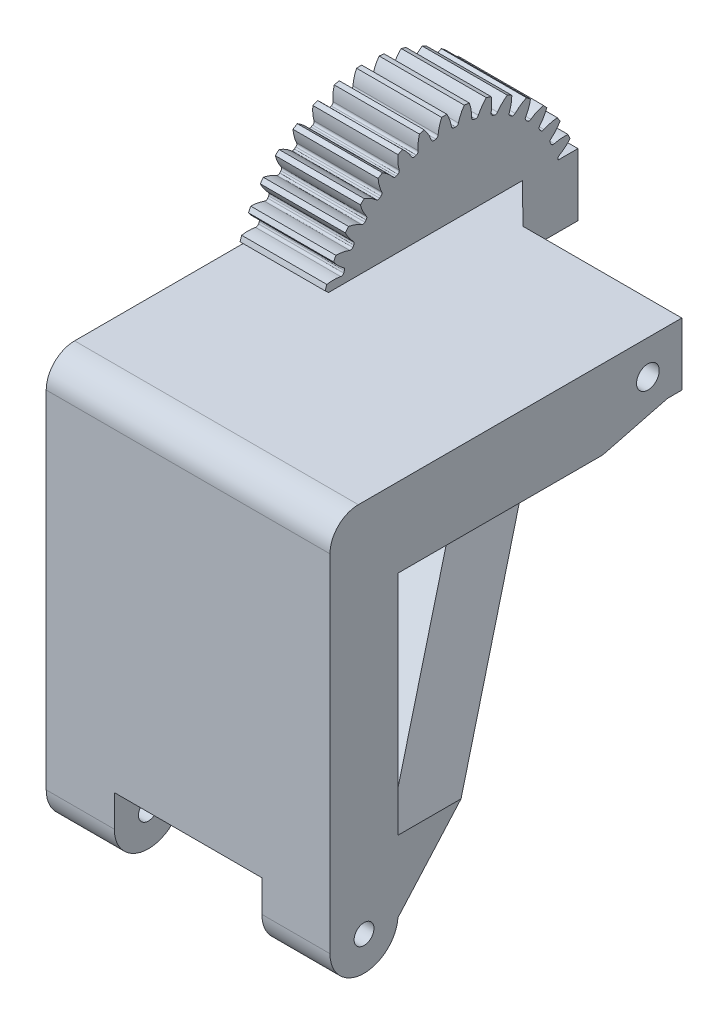
SolidWorks part; units mm, degrees
ref_plane "Front Plane" through (0, 0, 0) normal (0, 0, 1) x (1, 0, 0)
ref_plane "Top Plane" through (0, 0, 0) normal (0, 1, 0) x (1, 0, 0)
ref_plane "Right Plane" through (0, 0, 0) normal (1, 0, 0) x (0, 0, -1)
other "Graphic1"
sketch "Sketch2" plane through (0, 0, 0) normal (1, 0, 0) x (0, 0, -1)
  line L0 (-282, -50) -> (-282, 16.0062)
  line L1 (-282, 16.0062) -> (-203.3277, 16.0062)
  line L2 (-203.3277, 16.0062) -> (-203.3277, 4.9936)
  line L3 (-203.3277, 4.9936) -> (-222.5466, 4.9936)
  line L4 (-222.5466, 4.9936) -> (-233.9331, 2.0714)
  line L5 (-233.9331, 2.0714) -> (-233.9331, -9.6765)
  line L6 (-233.9331, -9.6765) -> (-270.0186, -50.4726)
  line L7 (-270.0186, 2.0714) -> (-270.0186, -35.8156)
  line L8 (-270.0186, -35.8156) -> (-240.3653, -2.4074)
  line L10 (-240.3653, -2.4074) -> (-240.3737, 1.8611)
  line L11 (-240.3737, 1.8611) -> (-270.0186, 2.0714)
  circle A0 centre (-276, -50) radius 1.75
  circle A1 centre (-226, 10) radius 2
  arc A2 (-282, -50) -> (-270.0186, -50.4726) centre (-276, -50) ccw
extrude "Boss-Extrude1" add sketch "Sketch2" along normal blind 47.5 and the other way blind 2.5 from offset 70
sketch "Sketch3" plane through (0, 0, 0) normal (0, 0, 1) x (1, 0, 0)
  line L0 (79.5, -55.8916) -> (79.5, -57.717)
  line L2 (79.5, -55.8916) -> (79.5, -44.4098)
  line L3 (79.5, -44.4098) -> (105.5, -44.4098)
  line L4 (105.5, -55.8916) -> (105.5, -44.4098)
  line L5 (79.5, -57.717) -> (105.5, -57.717)
  line L6 (105.5, -57.717) -> (105.5, -55.8916)
extrude "Cut-Extrude1" cut sketch "Sketch3" along normal through all
sketch "Sketch4" plane through (0, 0, 0) normal (0, 0, 1) x (1, 0, 0)
  line L0 (105.5, -44.4098) -> (94.3961, -22.2019)
  line L3 (90.6039, -22.2019) -> (79.5, -44.4098)
  line L4 (79.5, -44.4098) -> (105.5, -44.4098)
  line L5 (97.5, 2.0714) -> (117.5, -37.9286)
  line L6 (67.5, 2.0714) -> (117.5, 2.0714) construction
  line L7 (117.5, -50.4726) -> (117.5, -9.6765) construction
  line L8 (117.5, 2.0714) -> (97.5, 2.0714)
  line L9 (87.5, 2.0714) -> (67.5, 2.0714)
  line L10 (67.5, -9.6765) -> (67.5, 2.0714) construction
  line L11 (67.5, 2.0714) -> (67.5, -37.9286)
  line L12 (67.5, -50.4726) -> (67.5, -9.6765) construction
  line L13 (67.5, -37.9286) -> (87.5, 2.0714)
  line L14 (117.5, 2.0714) -> (117.5, -37.9286)
  line L15 (92.5, 16.0062) -> (92.5, -62.4116) construction
  line L16 (67.5, 16.0062) -> (117.5, 16.0062) construction
  line L17 (67.5, 16.0062) -> (67.5, -50) construction
  line L18 (117.5, 16.0062) -> (117.5, -50) construction
  arc A0 (94.3961, -22.2019) -> (90.6039, -22.2019) centre (92.5, -23.15) ccw
  dimension "D1" = 25
  dimension "D2" = 25
  dimension "D3" = 20
  dimension "D4" = 20
  dimension "D5" = 40
  dimension "D6" = 40
extrude "Cut-Extrude2" cut sketch "Sketch4" against normal blind 53 from surface at 270.0186 starting at face at (92.5, -16.8721, 270.0186)
fillet "Fillet1" radius 5 1 edges at (92.5, 16.0062, 282)
sketch "Sketch5" plane through (0, 16.0062, 0) normal (0, 1, 0) x (1, 0, 0)
  line L0 (65.0251, -220.0274) -> (95.5, -220.0314)
  line L1 (95.5, -220.0314) -> (102.5, -213.068)
  line L2 (102.5, -213.068) -> (102.5, -196.177)
  line L3 (102.5, -196.177) -> (65.0251, -196.177)
  line L4 (65.0251, -196.177) -> (65.0251, -220.0274)
extrude "Cut-Extrude3" cut sketch "Sketch5" against normal through all
sketch "Sketch7" plane through (117.5, 0, 0) normal (1, 0, 0) x (0, 0, -1)
  line L5 (-247.2493, 16.0062) -> (-206.8184, 16.0062)
  arc A0 (-222.9056, 32.589) -> (-222.459, 32.5234) centre (-226, 10) cw
  arc A1 (-221.7033, 29.6354) -> (-221.3907, 29.5644) centre (-226, 10) cw
  arc A2 (-219.0301, 31.7085) -> (-219.4613, 31.8423) centre (-226, 10) ccw
  arc A3 (-219.0301, 31.7085) -> (-218.6017, 31.5663) centre (-226, 10) cw
  arc A4 (-218.3589, 28.591) -> (-218.0634, 28.4667) centre (-226, 10) cw
  arc A5 (-215.3663, 30.1684) -> (-215.7678, 30.375) centre (-226, 10) ccw
  arc A6 (-215.3663, 30.1684) -> (-214.9691, 29.9539) centre (-226, 10) cw
  arc A7 (-215.2467, 26.9817) -> (-214.9773, 26.808) centre (-226, 10) cw
  arc A8 (-212.0257, 28.0155) -> (-212.3851, 28.2887) centre (-226, 10) ccw
  arc A9 (-212.0257, 28.0155) -> (-211.6717, 27.7353) centre (-226, 10) cw
  arc A10 (-212.4612, 24.8564) -> (-212.226, 24.6386) centre (-226, 10) cw
  arc A11 (-209.1096, 25.3152) -> (-209.4162, 25.6466) centre (-226, 10) ccw
  arc A12 (-209.1096, 25.3152) -> (-208.8097, 24.9778) centre (-226, 10) cw
  arc A13 (-210.0871, 22.2797) -> (-209.8933, 22.0244) centre (-226, 10) cw
  arc A14 (-206.7068, 22.1495) -> (-206.9511, 22.5292) centre (-226, 10) ccw
  arc A15 (-206.7068, 22.1495) -> (-206.47, 21.7652) centre (-226, 10) cw
  arc A16 (-208.1966, 19.3299) -> (-208.05, 19.0448) centre (-226, 10) cw
  arc A17 (-204.8901, 18.6147) -> (-205.0648, 19.031) centre (-226, 10) ccw
  arc A18 (-204.8901, 18.6147) -> (-204.7237, 18.1951) centre (-226, 10) cw
  arc A19 (-206.8469, 16.0966) -> (-206.8184, 16.0062) centre (-226, 10) cw
  arc A83 (-247.7085, 16.9699) -> (-247.8423, 16.5387) centre (-226, 10) ccw
  arc A84 (-247.7085, 16.9699) -> (-247.5663, 17.3984) centre (-226, 10) cw
  arc A85 (-244.591, 17.6411) -> (-244.4667, 17.9366) centre (-226, 10) cw
  arc A86 (-246.1684, 20.6337) -> (-246.375, 20.2323) centre (-226, 10) ccw
  arc A87 (-246.1684, 20.6337) -> (-245.9539, 21.0309) centre (-226, 10) cw
  arc A88 (-242.9817, 20.7533) -> (-242.808, 21.0228) centre (-226, 10) cw
  arc A89 (-244.0155, 23.9743) -> (-244.2887, 23.6149) centre (-226, 10) ccw
  arc A90 (-244.0155, 23.9743) -> (-243.7353, 24.3283) centre (-226, 10) cw
  arc A91 (-240.8564, 23.5388) -> (-240.6386, 23.774) centre (-226, 10) cw
  arc A92 (-241.3152, 26.8904) -> (-241.6466, 26.5838) centre (-226, 10) ccw
  arc A93 (-241.3152, 26.8904) -> (-240.9778, 27.1903) centre (-226, 10) cw
  arc A94 (-238.2797, 25.9129) -> (-238.0244, 26.1067) centre (-226, 10) cw
  arc A95 (-238.1495, 29.2932) -> (-238.5292, 29.0489) centre (-226, 10) ccw
  arc A96 (-238.1495, 29.2932) -> (-237.7652, 29.53) centre (-226, 10) cw
  arc A97 (-235.3299, 27.8035) -> (-235.0448, 27.95) centre (-226, 10) cw
  arc A98 (-234.6147, 31.1099) -> (-235.031, 30.9352) centre (-226, 10) ccw
  arc A99 (-234.6147, 31.1099) -> (-234.1951, 31.2763) centre (-226, 10) cw
  arc A100 (-232.0966, 29.1531) -> (-231.7904, 29.2479) centre (-226, 10) cw
  arc A101 (-230.8182, 32.2851) -> (-231.2585, 32.1853) centre (-226, 10) ccw
  arc A102 (-230.8182, 32.2851) -> (-230.376, 32.3761) centre (-226, 10) cw
  arc A103 (-228.6781, 29.9208) -> (-228.3601, 29.961) centre (-226, 10) cw
  arc A104 (-226.8752, 32.7832) -> (-227.3261, 32.7614) centre (-226, 10) ccw
  arc A105 (-226.8752, 32.7832) -> (-226.4239, 32.7961) centre (-226, 10) cw
  arc A106 (-225.1782, 30.0832) -> (-224.858, 30.0675) centre (-226, 10) cw
  arc A107 (-222.9056, 32.589) -> (-223.3535, 32.6459) centre (-226, 10) ccw
  arc A108 (-206.0792, 12.6781) -> (-206.039, 12.3601) centre (-226, 10) cw [skipped]
  arc A109 (-203.2168, 10.8752) -> (-203.2386, 11.3261) centre (-226, 10) ccw [skipped]
  arc A110 (-203.2168, 10.8752) -> (-203.2039, 10.4239) centre (-226, 10) cw [skipped]
  arc A111 (-205.9168, 9.1782) -> (-205.9325, 8.858) centre (-226, 10) cw [skipped]
  arc A112 (-203.411, 6.9056) -> (-203.3541, 7.3535) centre (-226, 10) ccw [skipped]
  arc A113 (-203.411, 6.9056) -> (-203.4767, 6.459) centre (-226, 10) cw [skipped]
  arc A114 (-206.3646, 5.7033) -> (-206.4356, 5.3907) centre (-226, 10) cw [skipped]
  arc A115 (-204.2915, 3.0301) -> (-204.1577, 3.4613) centre (-226, 10) ccw [skipped]
  arc A116 (-204.2915, 3.0301) -> (-204.4337, 2.6017) centre (-226, 10) cw [skipped]
  arc A117 (-207.4091, 2.3589) -> (-207.5333, 2.0634) centre (-226, 10) cw [skipped]
  arc A118 (-205.8316, -0.6337) -> (-205.625, -0.2322) centre (-226, 10) ccw [skipped]
  arc A119 (-205.8316, -0.6337) -> (-206.0461, -1.0309) centre (-226, 10) cw [skipped]
  arc A120 (-209.0184, -0.7533) -> (-209.192, -1.0227) centre (-226, 10) cw [skipped]
  arc A121 (-207.9845, -3.9743) -> (-207.7114, -3.6149) centre (-226, 10) ccw [skipped]
  arc A122 (-207.9845, -3.9743) -> (-208.2647, -4.3283) centre (-226, 10) cw [skipped]
  arc A123 (-211.1436, -3.5388) -> (-211.3614, -3.774) centre (-226, 10) cw [skipped]
  arc A124 (-210.6848, -6.8904) -> (-210.3534, -6.5838) centre (-226, 10) ccw [skipped]
  arc A125 (-210.6848, -6.8904) -> (-211.0222, -7.1903) centre (-226, 10) cw [skipped]
  arc A126 (-213.7203, -5.9129) -> (-213.9757, -6.1067) centre (-226, 10) cw [skipped]
  arc A127 (-213.8505, -9.2932) -> (-213.4709, -9.0489) centre (-226, 10) ccw [skipped]
  arc A128 (-213.8505, -9.2932) -> (-214.2348, -9.53) centre (-226, 10) cw [skipped]
  arc A129 (-216.6701, -7.8035) -> (-216.9552, -7.95) centre (-226, 10) cw [skipped]
  arc A130 (-217.3853, -11.1099) -> (-216.969, -10.9352) centre (-226, 10) ccw [skipped]
  arc A131 (-217.3853, -11.1099) -> (-217.8049, -11.2763) centre (-226, 10) cw [skipped]
  arc A132 (-219.9034, -9.1531) -> (-220.2096, -9.2479) centre (-226, 10) cw [skipped]
  arc A133 (-221.1818, -12.2851) -> (-220.7416, -12.1853) centre (-226, 10) ccw [skipped]
  arc A134 (-221.1818, -12.2851) -> (-221.624, -12.3761) centre (-226, 10) cw [skipped]
  arc A135 (-223.3219, -9.9208) -> (-223.6399, -9.961) centre (-226, 10) cw [skipped]
  arc A136 (-225.1248, -12.7832) -> (-224.6739, -12.7614) centre (-226, 10) ccw [skipped]
  arc A137 (-225.1248, -12.7832) -> (-225.5761, -12.7961) centre (-226, 10) cw [skipped]
  arc A138 (-226.8218, -10.0832) -> (-227.142, -10.0675) centre (-226, 10) cw [skipped]
  arc A139 (-229.0944, -12.589) -> (-228.6465, -12.6459) centre (-226, 10) ccw [skipped]
  arc A140 (-229.0944, -12.589) -> (-229.541, -12.5233) centre (-226, 10) cw [skipped]
  arc A141 (-230.2967, -9.6354) -> (-230.6093, -9.5644) centre (-226, 10) cw [skipped]
  arc A142 (-232.9699, -11.7085) -> (-232.5387, -11.8423) centre (-226, 10) ccw [skipped]
  arc A143 (-232.9699, -11.7085) -> (-233.3984, -11.5663) centre (-226, 10) cw [skipped]
  arc A144 (-233.6411, -8.591) -> (-233.9366, -8.4667) centre (-226, 10) cw [skipped]
  arc A145 (-236.6337, -10.1684) -> (-236.2323, -10.375) centre (-226, 10) ccw [skipped]
  arc A146 (-236.6337, -10.1684) -> (-237.0309, -9.9539) centre (-226, 10) cw [skipped]
  arc A147 (-236.7533, -6.9817) -> (-237.0228, -6.808) centre (-226, 10) cw [skipped]
  arc A148 (-239.9743, -8.0155) -> (-239.6149, -8.2887) centre (-226, 10) ccw [skipped]
  arc A149 (-239.9743, -8.0155) -> (-240.3283, -7.7353) centre (-226, 10) cw [skipped]
  arc A150 (-239.5388, -4.8564) -> (-239.774, -4.6386) centre (-226, 10) cw [skipped]
  arc A151 (-242.8904, -5.3152) -> (-242.5838, -5.6466) centre (-226, 10) ccw [skipped]
  arc A152 (-242.8904, -5.3152) -> (-243.1903, -4.9778) centre (-226, 10) cw [skipped]
  arc A153 (-241.9129, -2.2797) -> (-242.1067, -2.0244) centre (-226, 10) cw [skipped]
  arc A154 (-245.2932, -2.1495) -> (-245.0489, -2.5291) centre (-226, 10) ccw [skipped]
  arc A155 (-245.2932, -2.1495) -> (-245.53, -1.7652) centre (-226, 10) cw [skipped]
  arc A156 (-243.8035, 0.6701) -> (-243.95, 0.9552) centre (-226, 10) cw [skipped]
  arc A157 (-247.1099, 1.3853) -> (-246.9352, 0.969) centre (-226, 10) ccw [skipped]
  arc A158 (-247.1099, 1.3853) -> (-247.2763, 1.8049) centre (-226, 10) cw [skipped]
  arc A159 (-245.1531, 3.9034) -> (-245.2479, 4.2096) centre (-226, 10) cw [skipped]
  arc A160 (-248.2851, 5.1818) -> (-248.1853, 4.7416) centre (-226, 10) ccw [skipped]
  arc A161 (-248.2851, 5.1818) -> (-248.3761, 5.624) centre (-226, 10) cw [skipped]
  arc A162 (-245.9208, 7.3219) -> (-245.961, 7.6399) centre (-226, 10) cw [skipped]
  arc A163 (-248.7832, 9.1248) -> (-248.7614, 8.6739) centre (-226, 10) ccw [skipped]
  arc A164 (-248.7832, 9.1248) -> (-248.7961, 9.5761) centre (-226, 10) cw [skipped]
  arc A165 (-246.0832, 10.8218) -> (-246.0675, 11.142) centre (-226, 10) cw [skipped]
  arc A166 (-248.5891, 13.0944) -> (-248.6459, 12.6465) centre (-226, 10) ccw [skipped]
  arc A167 (-248.5891, 13.0944) -> (-248.5234, 13.541) centre (-226, 10) cw [skipped]
  arc A168 (-245.6354, 14.2967) -> (-245.5644, 14.6093) centre (-226, 10) cw [skipped]
  arc A169 (-203.7149, 14.8182) -> (-203.8147, 15.2584) centre (-226, 10) ccw [skipped]
  arc A170 (-203.7149, 14.8182) -> (-203.6239, 14.376) centre (-226, 10) cw [skipped]
  spline S0 degree 2 poles (-222.459, 32.5234) (-222.0472, 31.3598) (-222.0503, 30.123) knots 0 0 0 1 1 1
  spline S1 degree 2 poles (-222.0503, 30.123) (-222.0649, 29.7407) (-221.7033, 29.6354) knots 0 0 0 1 1 1
  spline S2 degree 2 poles (-220.867, 29.8542) (-221.019, 29.503) (-221.3907, 29.5644) knots 0 0 0 1 1 1
  spline S3 degree 2 poles (-219.4613, 31.8423) (-220.3354, 30.9709) (-220.867, 29.8542) knots 0 0 0 1 1 1
  spline S4 degree 2 poles (-218.6017, 31.5663) (-218.3982, 30.3489) (-218.616, 29.1315) knots 0 0 0 1 1 1
  spline S5 degree 2 poles (-218.616, 29.1315) (-218.6968, 28.7574) (-218.3589, 28.591) knots 0 0 0 1 1 1
  spline S6 degree 2 poles (-217.4973, 28.6612) (-217.708, 28.3418) (-218.0634, 28.4667) knots 0 0 0 1 1 1
  spline S7 degree 2 poles (-215.7678, 30.375) (-216.7799, 29.6687) (-217.4973, 28.6612) knots 0 0 0 1 1 1
  spline S8 degree 2 poles (-214.9691, 29.9539) (-214.9801, 28.7197) (-215.4061, 27.5586) knots 0 0 0 1 1 1
  spline S9 degree 2 poles (-215.4061, 27.5586) (-215.5506, 27.2043) (-215.2467, 26.9817) knots 0 0 0 1 1 1
  spline S10 degree 2 poles (-214.386, 26.9012) (-214.649, 26.6233) (-214.9773, 26.808) knots 0 0 0 1 1 1
  spline S11 degree 2 poles (-212.3851, 28.2887) (-213.5046, 27.7688) (-214.386, 26.9012) knots 0 0 0 1 1 1
  spline S12 degree 2 poles (-211.6717, 27.7353) (-211.8969, 26.5217) (-212.518, 25.4522) knots 0 0 0 1 1 1
  spline S13 degree 2 poles (-212.518, 25.4522) (-212.7218, 25.1284) (-212.4612, 24.8564) knots 0 0 0 1 1 1
  spline S14 degree 2 poles (-211.6276, 24.6277) (-211.9348, 24.3996) (-212.226, 24.6386) knots 0 0 0 1 1 1
  spline S15 degree 2 poles (-209.4162, 25.6466) (-210.6089, 25.329) (-211.6276, 24.6277) knots 0 0 0 1 1 1
  spline S16 degree 2 poles (-208.8097, 24.9778) (-209.2422, 23.8217) (-210.0396, 22.8763) knots 0 0 0 1 1 1
  spline S17 degree 2 poles (-210.0396, 22.8763) (-210.2965, 22.5928) (-210.0871, 22.2797) knots 0 0 0 1 1 1
  spline S18 degree 2 poles (-209.3059, 21.9097) (-209.6481, 21.7385) (-209.8933, 22.0244) knots 0 0 0 1 1 1
  spline S19 degree 2 poles (-206.9511, 22.5292) (-208.1808, 22.4235) (-209.3059, 21.9097) knots 0 0 0 1 1 1
  spline S20 degree 2 poles (-206.47, 21.7652) (-207.0966, 20.7018) (-208.0461, 19.9092) knots 0 0 0 1 1 1
  spline S21 degree 2 poles (-208.0461, 19.9092) (-208.3484, 19.6746) (-208.1966, 19.3299) knots 0 0 0 1 1 1
  spline S22 degree 2 poles (-207.4914, 18.8299) (-207.8581, 18.7207) (-208.05, 19.0448) knots 0 0 0 1 1 1
  spline S23 degree 2 poles (-205.0648, 19.031) (-206.2942, 19.1405) (-207.4914, 18.8299) knots 0 0 0 1 1 1
  spline S24 degree 2 poles (-204.7237, 18.1951) (-205.5255, 17.2567) (-206.5981, 16.641) knots 0 0 0 1 1 1
  spline S25 degree 2 poles (-206.5981, 16.641) (-206.9366, 16.4625) (-206.8469, 16.0966) knots 0 0 0 1 1 1
  spline S111 degree 2 poles (-247.8423, 16.5387) (-247.5588, 16.2543) (-247.2493, 16.0062) knots 0 0 0 0.325355 0.325355 0.325355
  spline S112 degree 2 poles (-247.5663, 17.3984) (-246.3489, 17.6019) (-245.1315, 17.384) knots 0 0 0 1 1 1
  spline S113 degree 2 poles (-245.1315, 17.384) (-244.7574, 17.3032) (-244.591, 17.6411) knots 0 0 0 1 1 1
  spline S114 degree 2 poles (-244.6612, 18.5027) (-244.3418, 18.292) (-244.4667, 17.9366) knots 0 0 0 1 1 1
  spline S115 degree 2 poles (-246.375, 20.2323) (-245.6687, 19.2201) (-244.6612, 18.5027) knots 0 0 0 1 1 1
  spline S116 degree 2 poles (-245.9539, 21.0309) (-244.7197, 21.0199) (-243.5586, 20.594) knots 0 0 0 1 1 1
  spline S117 degree 2 poles (-243.5586, 20.594) (-243.2043, 20.4494) (-242.9817, 20.7533) knots 0 0 0 1 1 1
  spline S118 degree 2 poles (-242.9012, 21.614) (-242.6233, 21.351) (-242.808, 21.0228) knots 0 0 0 1 1 1
  spline S119 degree 2 poles (-244.2887, 23.6149) (-243.7688, 22.4954) (-242.9012, 21.614) knots 0 0 0 1 1 1
  spline S120 degree 2 poles (-243.7353, 24.3283) (-242.5217, 24.1031) (-241.4522, 23.482) knots 0 0 0 1 1 1
  spline S121 degree 2 poles (-241.4522, 23.482) (-241.1284, 23.2782) (-240.8564, 23.5388) knots 0 0 0 1 1 1
  spline S122 degree 2 poles (-240.6277, 24.3724) (-240.3996, 24.0652) (-240.6386, 23.774) knots 0 0 0 1 1 1
  spline S123 degree 2 poles (-241.6466, 26.5838) (-241.3291, 25.3911) (-240.6277, 24.3724) knots 0 0 0 1 1 1
  spline S124 degree 2 poles (-240.9778, 27.1903) (-239.8218, 26.7579) (-238.8763, 25.9605) knots 0 0 0 1 1 1
  spline S125 degree 2 poles (-238.8763, 25.9605) (-238.5928, 25.7035) (-238.2797, 25.9129) knots 0 0 0 1 1 1
  spline S126 degree 2 poles (-237.9097, 26.6941) (-237.7385, 26.352) (-238.0244, 26.1067) knots 0 0 0 1 1 1
  spline S127 degree 2 poles (-238.5292, 29.0489) (-238.4235, 27.8192) (-237.9097, 26.6941) knots 0 0 0 1 1 1
  spline S128 degree 2 poles (-237.7652, 29.53) (-236.7018, 28.9034) (-235.9092, 27.9539) knots 0 0 0 1 1 1
  spline S129 degree 2 poles (-235.9092, 27.9539) (-235.6746, 27.6516) (-235.3299, 27.8035) knots 0 0 0 1 1 1
  spline S130 degree 2 poles (-234.8299, 28.5086) (-234.7207, 28.1419) (-235.0448, 27.95) knots 0 0 0 1 1 1
  spline S131 degree 2 poles (-235.031, 30.9352) (-235.1405, 29.7058) (-234.8299, 28.5086) knots 0 0 0 1 1 1
  spline S132 degree 2 poles (-234.1951, 31.2763) (-233.2567, 30.4745) (-232.641, 29.4019) knots 0 0 0 1 1 1
  spline S133 degree 2 poles (-232.641, 29.4019) (-232.4625, 29.0634) (-232.0966, 29.1531) knots 0 0 0 1 1 1
  spline S134 degree 2 poles (-231.4818, 29.7607) (-231.4379, 29.3806) (-231.7904, 29.2479) knots 0 0 0 1 1 1
  spline S135 degree 2 poles (-231.2585, 32.1853) (-231.5798, 30.9936) (-231.4818, 29.7607) knots 0 0 0 1 1 1
  spline S136 degree 2 poles (-230.376, 32.3761) (-229.5911, 31.4236) (-229.171, 30.2603) knots 0 0 0 1 1 1
  spline S137 degree 2 poles (-229.171, 30.2603) (-229.054, 29.896) (-228.6781, 29.9208) knots 0 0 0 1 1 1
  spline S138 degree 2 poles (-227.9671, 30.4124) (-227.9899, 30.0304) (-228.3601, 29.961) knots 0 0 0 1 1 1
  spline S139 degree 2 poles (-227.3261, 32.7614) (-227.8495, 31.6436) (-227.9671, 30.4124) knots 0 0 0 1 1 1
  spline S140 degree 2 poles (-226.4239, 32.7961) (-225.8163, 31.7217) (-225.6047, 30.5032) knots 0 0 0 1 1 1
  spline S141 degree 2 poles (-225.6047, 30.5032) (-225.5527, 30.1241) (-225.1782, 30.0832) knots 0 0 0 1 1 1
  spline S142 degree 2 poles (-224.3926, 30.4439) (-224.4814, 30.0717) (-224.858, 30.0675) knots 0 0 0 1 1 1
  spline S143 degree 2 poles (-223.3535, 32.6459) (-224.063, 31.636) (-224.3926, 30.4439) knots 0 0 0 1 1 1
  dimension "D6" = 36
extrude "Boss-Extrude2" add sketch "Sketch7" against normal blind 15
mirror "Mirror2" about plane through (67.5, -50, 276) normal (1, 0, 0) of "Boss-Extrude2", "Cut-Extrude3", "Fillet1", "Cut-Extrude2", "Cut-Extrude1", "Boss-Extrude1"
sketch "Sketch8" plane through (-0.0286, 0, 220.019) normal (0.0001, 0, -1) x (-1, 0, -0.0001)
  line L0 (-67.5286, 16.0062) -> (-67.5286, 48.941)
  line L1 (-67.5286, 48.941) -> (-128.158, 48.941)
  line L2 (-128.158, 48.941) -> (-128.158, -63.4601)
  line L3 (-128.158, -63.4601) -> (-67.5286, -63.4601)
  line L4 (-67.5286, -63.4601) -> (-67.5286, 16.0062)
extrude "Cut-Extrude4" cut sketch "Sketch8" against normal through all and the other way through all
